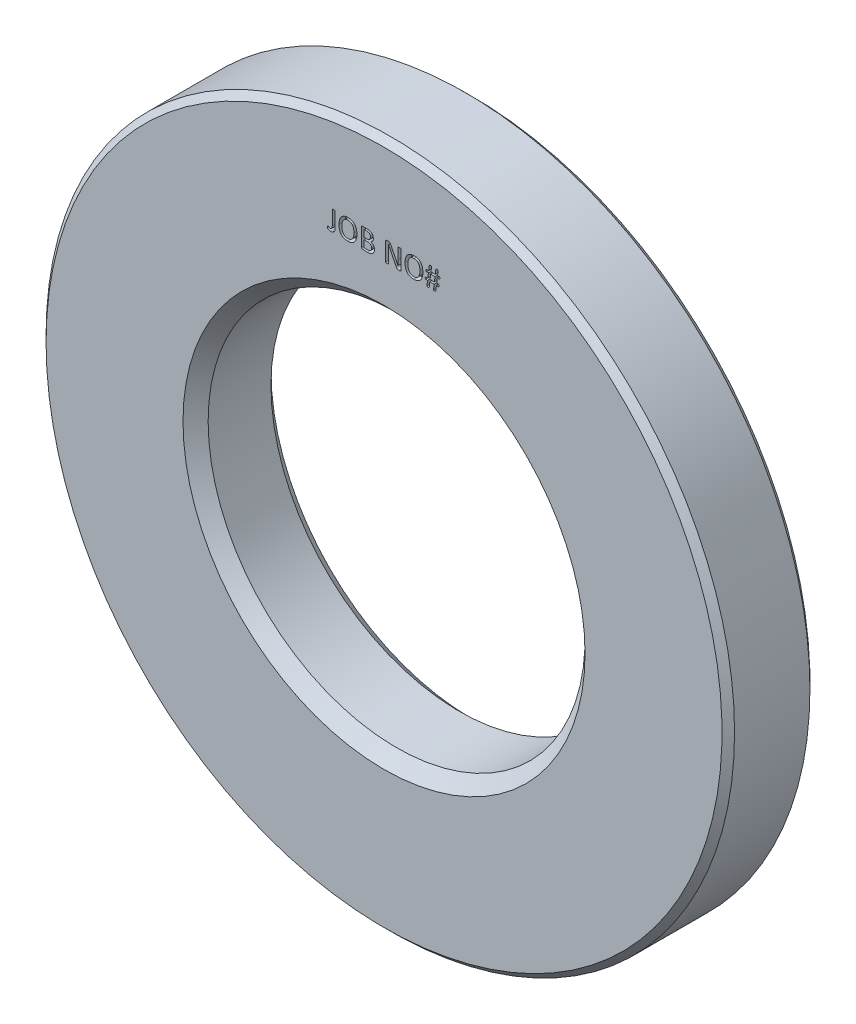
SolidWorks part; units mm, degrees
ref_plane "Front Plane" through (0, 0, 0) normal (0, 0, 1) x (1, 0, 0)
ref_plane "Top Plane" through (0, 0, 0) normal (0, 1, 0) x (1, 0, 0)
ref_plane "Right Plane" through (0, 0, 0) normal (1, 0, 0) x (0, 0, -1)
sketch "Sketch1" plane through (0, 0, 0) normal (1, 0, 0) x (0, 0, -1)
  line L0 (0, 0) -> (-7, 0) construction
  line L1 (-0.5, 27.4) -> (0, 26.9)
  line L2 (-0.5, 27.4) -> (-6.5, 27.4)
  line L3 (0, 26.9) -> (0, 16)
  line L4 (-1, 15) -> (-6, 15)
  line L5 (-7, 26.9) -> (-7, 16)
  line L6 (0, 16) -> (-1, 15)
  line L7 (-6, 15) -> (-7, 16)
  line L8 (-6.5, 27.4) -> (-7, 26.9)
  point P3 (0, 27.4)
  point P4 (-7, 15)
  point P5 (0, 15)
  point P6 (-7, 27.4)
  dimension "D1" = 54.8
  dimension "D2" = 30
  dimension "D3" = 7
revolve "Revolve1" add sketch "Sketch1" angle 360 about L0
sketch "Sketch2" plane through (0, 0, 7) normal (0, 0, 1) x (1, 0, 0)
  line L0 (-19.0423, 19) -> (19.0423, 19) construction
  circle A0 centre (0, 0) radius 26.9 construction
  text T0 "JOB NO#" font "Calibri" height in points 6
  dimension "D1" = 19
extrude "Cut-Extrude1" cut sketch "Sketch2" against normal blind 0.5
